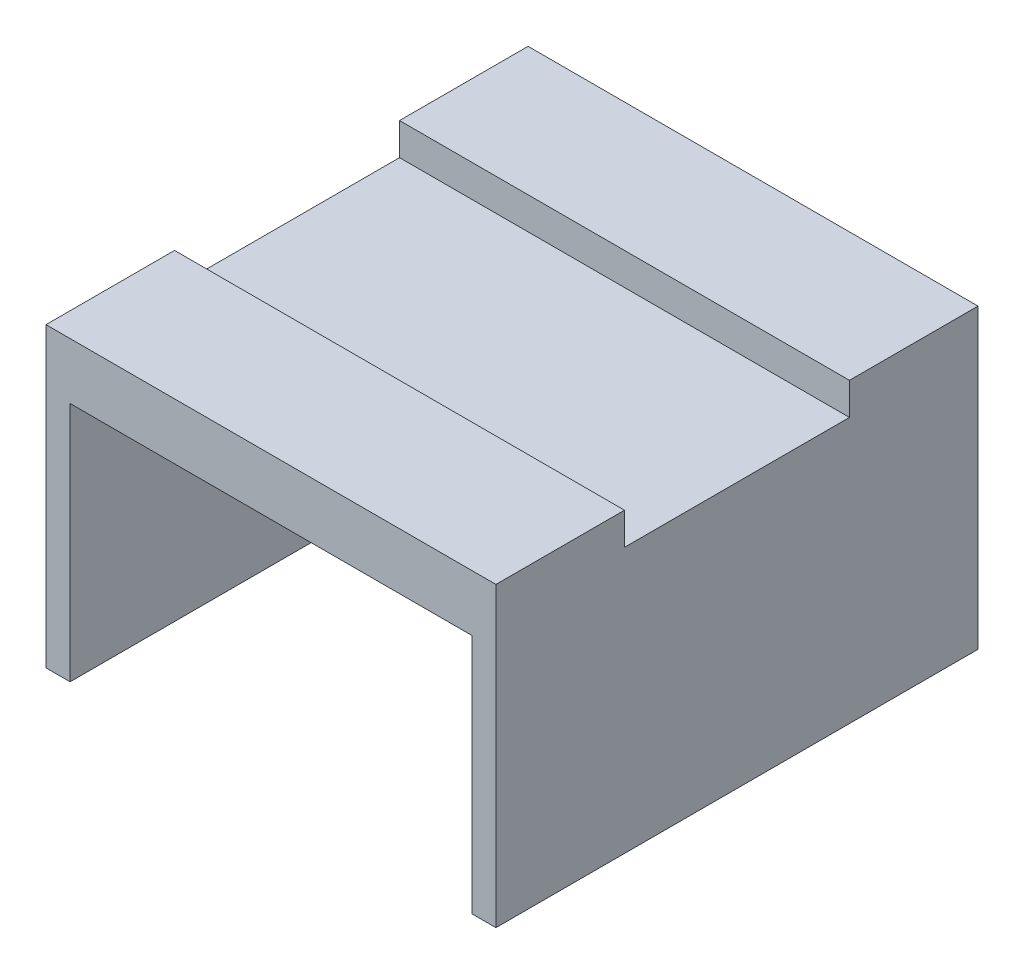
SolidWorks part; units mm, degrees
ref_plane "Front Plane" through (0, 0, 0) normal (0, 0, 1) x (1, 0, 0)
ref_plane "Top Plane" through (0, 0, 0) normal (0, 1, 0) x (1, 0, 0)
ref_plane "Right Plane" through (0, 0, 0) normal (1, 0, 0) x (0, 0, -1)
sketch "Sketch1" plane through (0, 0, 0) normal (0, 1, 0) x (1, 0, 0)
  line L1 (-11.4748, 7.6104) -> (13.5252, 7.6104)
  line L2 (-11.4748, 7.6104) -> (-11.4748, -22.3896)
  line L3 (-11.4748, -22.3896) -> (13.5252, -22.3896)
  line L4 (13.5252, 7.6104) -> (13.5252, -22.3896)
  line L5 (-11.4748, 7.6104) -> (-12.9748, 7.6104)
  line L6 (-11.4748, 7.6104) -> (-11.4748, -22.3896)
  line L7 (-11.4748, -22.3896) -> (-12.9748, -22.3896)
  line L8 (-12.9748, 7.6104) -> (-12.9748, -22.3896)
  line L9 (13.5252, 7.6104) -> (15.0252, 7.6104)
  line L10 (13.5252, 7.6104) -> (13.5252, -22.3896)
  line L11 (13.5252, -22.3896) -> (15.0252, -22.3896)
  line L12 (15.0252, 7.6104) -> (15.0252, -22.3896)
  dimension "D1" = 25
  dimension "D2" = 30
  dimension "D3" = 1.5
  dimension "D4" = 1.5
extrude "Boss-Extrude1" add sketch "Sketch1" along normal blind 15 contours L4 L11 L12 L9 | L5 L8 L7 L2
sketch "Sketch4" plane through (0, 15, 0) normal (0, 1, 0) x (1, 0, 0)
  line L1 (-12.9748, 7.6104) -> (15.0252, 7.6104)
  line L2 (-12.9748, 7.6104) -> (-12.9748, -22.3896)
  line L3 (-12.9748, -22.3896) -> (15.0252, -22.3896)
  line L4 (15.0252, 7.6104) -> (15.0252, -22.3896)
extrude "Boss-Extrude2" add sketch "Sketch4" along normal blind 1.5
sketch "Sketch5" plane through (0, 16.5, 0) normal (0, 1, 0) x (1, 0, 0)
  line L0 (15.0252, 7.6104) -> (-12.9748, 7.6104) construction
  line L1 (-12.9748, 7.6104) -> (15.0252, 7.6104)
  line L2 (-12.9748, 7.6104) -> (-12.9748, -0.3896)
  line L3 (-12.9748, -0.3896) -> (15.0252, -0.3896)
  line L4 (15.0252, 7.6104) -> (15.0252, -0.3896)
  line L5 (-12.9748, 7.6104) -> (-12.9748, -22.3896) construction
  line L6 (15.0252, -22.3896) -> (15.0252, 7.6104) construction
  line L8 (-12.9748, -22.3896) -> (15.0252, -22.3896)
  line L9 (-12.9748, -22.3896) -> (-12.9748, -14.3896)
  line L10 (-12.9748, -14.3896) -> (15.0252, -14.3896)
  line L11 (15.0252, -22.3896) -> (15.0252, -14.3896)
  dimension "D1" = 8
  dimension "D2" = 8
extrude "Boss-Extrude3" add sketch "Sketch5" along normal blind 2
